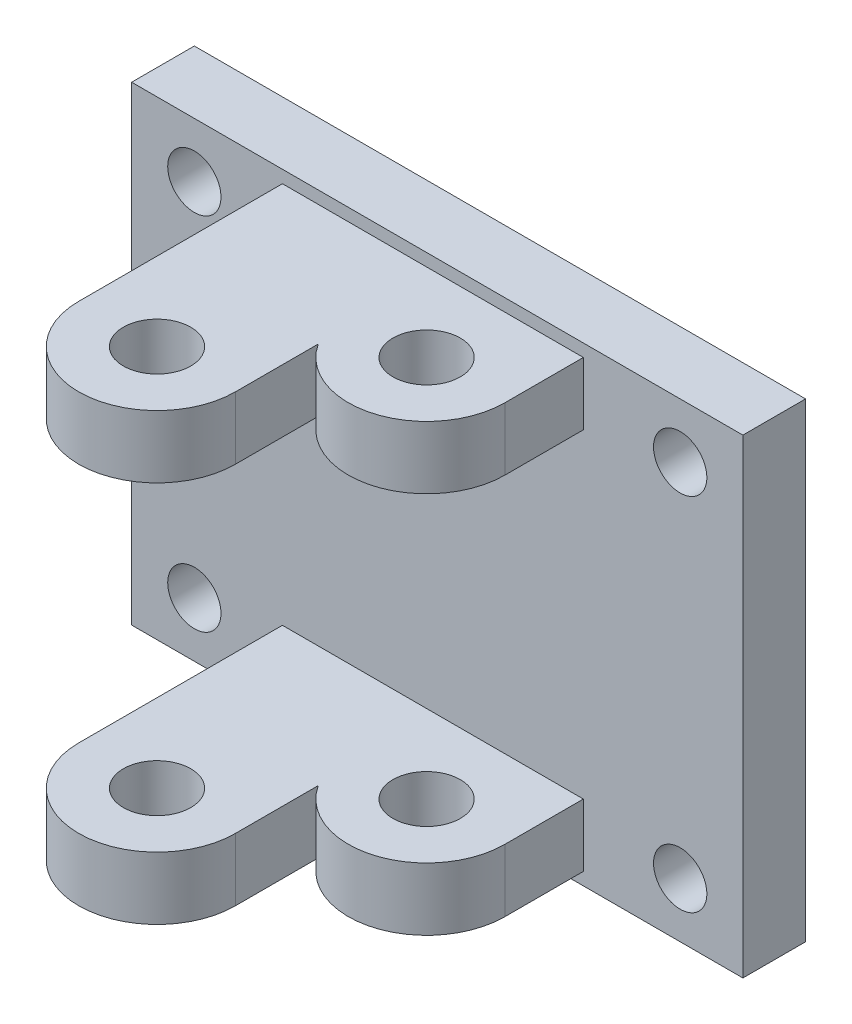
SolidWorks part; units mm, degrees
ref_plane "Front Plane" through (0, 0, 0) normal (0, 0, 1) x (1, 0, 0)
ref_plane "Top Plane" through (0, 0, 0) normal (0, 1, 0) x (1, 0, 0)
ref_plane "Right Plane" through (0, 0, 0) normal (1, 0, 0) x (0, 0, -1)
sketch "Removable_adapter_base_profile" plane through (0, 0, 0) normal (0, 0, 1) x (1, 0, 0)
  line L1 (23, -15) -> (62, -15)
  line L2 (23, -15) -> (23, 15)
  line L3 (23, 15) -> (62, 15)
  line L4 (62, -15) -> (62, 15)
  dimension "D1" = 39
  dimension "D2" = 30
extrude "Removable_adapter_base" add sketch "Removable_adapter_base_profile" along normal blind 4 from offset 4
sketch "Left_pin0_support_profile" plane through (0, 0, 0) normal (0, 1, 0) x (1, 0, 0)
  line L1 (32.6205, -21) -> (42.6205, -21)
  line L2 (32.6205, -21) -> (32.6205, -8)
  line L3 (32.6205, -8) -> (42.6205, -8)
  line L4 (42.6205, -21) -> (42.6205, -8)
  dimension "D1" = 10
  dimension "D2" = 13
extrude "Left_pin0_support" add sketch "Left_pin0_support_profile" along normal blind 4 from offset 10.2
sketch "Left_pin0_rounded_lug_profile" plane through (0, 0, 0) normal (0, 1, 0) x (1, 0, 0)
  circle A0 centre (37.6205, -21) radius 5
  dimension "D1" = 10
extrude "Left_pin0_rounded_lug" add sketch "Left_pin0_rounded_lug_profile" along normal blind 4 from offset 10.2
sketch "Left_pin1_support_profile" plane through (0, 0, 0) normal (0, 1, 0) x (1, 0, 0)
  line L1 (41.8205, -13) -> (51.8205, -13)
  line L2 (41.8205, -13) -> (41.8205, -8)
  line L3 (41.8205, -8) -> (51.8205, -8)
  line L4 (51.8205, -13) -> (51.8205, -8)
  dimension "D1" = 10
  dimension "D2" = 5
extrude "Left_pin1_support" add sketch "Left_pin1_support_profile" along normal blind 4 from offset 10.2
sketch "Left_pin1_rounded_lug_profile" plane through (0, 0, 0) normal (0, 1, 0) x (1, 0, 0)
  circle A0 centre (46.8205, -13) radius 5
  dimension "D1" = 10
extrude "Left_pin1_rounded_lug" add sketch "Left_pin1_rounded_lug_profile" along normal blind 4 from offset 10.2
sketch "Right_pin0_support_profile" plane through (0, 0, 0) normal (0, 1, 0) x (1, 0, 0)
  line L1 (32.6205, -21) -> (42.6205, -21)
  line L2 (32.6205, -21) -> (32.6205, -8)
  line L3 (32.6205, -8) -> (42.6205, -8)
  line L4 (42.6205, -21) -> (42.6205, -8)
  dimension "D1" = 10
  dimension "D2" = 13
extrude "Right_pin0_support" add sketch "Right_pin0_support_profile" along normal blind 4 from offset 14.2
sketch "Right_pin0_rounded_lug_profile" plane through (0, 0, 0) normal (0, 1, 0) x (1, 0, 0)
  circle A0 centre (37.6205, -21) radius 5
  dimension "D1" = 10
extrude "Right_pin0_rounded_lug" add sketch "Right_pin0_rounded_lug_profile" along normal blind 4 from offset 14.2
sketch "Right_pin1_support_profile" plane through (0, 0, 0) normal (0, 1, 0) x (1, 0, 0)
  line L1 (41.8205, -13) -> (51.8205, -13)
  line L2 (41.8205, -13) -> (41.8205, -8)
  line L3 (41.8205, -8) -> (51.8205, -8)
  line L4 (51.8205, -13) -> (51.8205, -8)
  dimension "D1" = 10
  dimension "D2" = 5
extrude "Right_pin1_support" add sketch "Right_pin1_support_profile" along normal blind 4 from offset 14.2
sketch "Right_pin1_rounded_lug_profile" plane through (0, 0, 0) normal (0, 1, 0) x (1, 0, 0)
  circle A0 centre (46.8205, -13) radius 5
  dimension "D1" = 10
extrude "Right_pin1_rounded_lug" add sketch "Right_pin1_rounded_lug_profile" along normal blind 4 from offset 14.2
sketch "Both_M4_gripper_pin_axes_profile" plane through (0, 0, 0) normal (0, 1, 0) x (1, 0, 0)
  circle A0 centre (37.6205, -21) radius 2.15
  circle A1 centre (46.8205, -13) radius 2.15
  dimension "D1" = 4.3
  dimension "D2" = 4.3
extrude "Both_M4_gripper_pin_axes" cut sketch "Both_M4_gripper_pin_axes_profile" along normal through all from offset 20
sketch "Four_M3_removable_deck_bolts_profile" plane through (0, 0, 0) normal (0, 0, 1) x (1, 0, 0)
  circle A0 centre (27, -11.5) radius 1.7
  circle A1 centre (27, 11.5) radius 1.7
  circle A2 centre (58, -11.5) radius 1.7
  circle A3 centre (58, 11.5) radius 1.7
  dimension "D1" = 3.4
  dimension "D2" = 3.4
  dimension "D3" = 3.4
  dimension "D4" = 3.4
extrude "Four_M3_removable_deck_bolts" cut sketch "Four_M3_removable_deck_bolts_profile" along normal through all from offset 50
